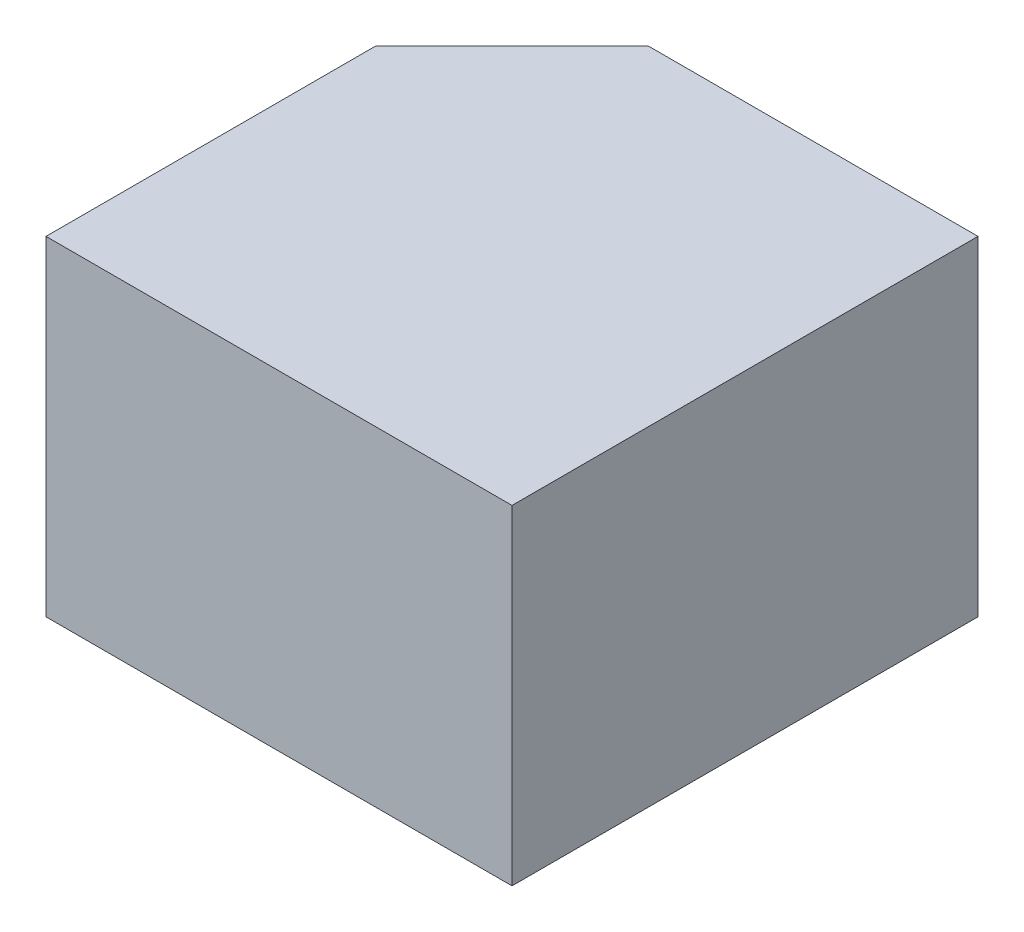
SolidWorks part; units mm, degrees
ref_plane "Front Plane" through (0, 0, 0) normal (0, 0, 1) x (1, 0, 0)
ref_plane "Top Plane" through (0, 0, 0) normal (0, 1, 0) x (1, 0, 0)
ref_plane "Right Plane" through (0, 0, 0) normal (1, 0, 0) x (0, 0, -1)
sketch "Sketch6" plane through (0, 0, 0) normal (0, 1, 0) x (1, 0, 0)
  line L0 (-14.1421, -14.1421) -> (14.1421, 14.1421) construction
  line L1 (21.2132, -21.2132) -> (-21.2132, -21.2132)
  line L2 (21.2132, -21.2132) -> (21.2132, 21.2132)
  line L3 (21.2132, 21.2132) -> (-21.2132, 21.2132)
  line L4 (-21.2132, -21.2132) -> (-21.2132, 21.2132)
  line L5 (21.2132, -21.2132) -> (-21.2132, 21.2132) construction
  line L6 (21.2132, 21.2132) -> (-21.2132, -21.2132) construction
  line L7 (14.1421, 14.1421) -> (21.2132, 7.0711)
  line L8 (14.1421, 14.1421) -> (7.0711, 21.2132)
  line L9 (-14.1421, -14.1421) -> (-21.2132, -7.0711)
  line L10 (-14.1421, -14.1421) -> (-7.0711, -21.2132)
  line L11 (-15, 15) -> (-8.7868, 21.2132)
  line L12 (-15, 15) -> (-21.2132, 8.7868)
  circle A0 centre (0, 0) radius 21.2132
  point P0 (0, 0)
  point P9 (0, 0)
  point P17 (-21.2132, 9.0311)
  dimension "D1" = 10
  dimension "D3" = 40
extrude "Boss-Extrude4" add sketch "Sketch6" along normal blind 30 contours L2 L1 L4 L3
sketch "Sketch7" plane through (0, 0, 0) normal (0, -1, 0) x (1, 0, 0)
  line L0 (-21.2132, -8.7868) -> (-8.7868, -21.2132)
  line L1 (-8.7868, -21.2132) -> (-21.2132, -21.2132)
  line L2 (-21.2132, -21.2132) -> (-21.2132, -8.7868)
extrude "Cut-Extrude2" cut sketch "Sketch7" against normal through all contours L2 L0 L1
